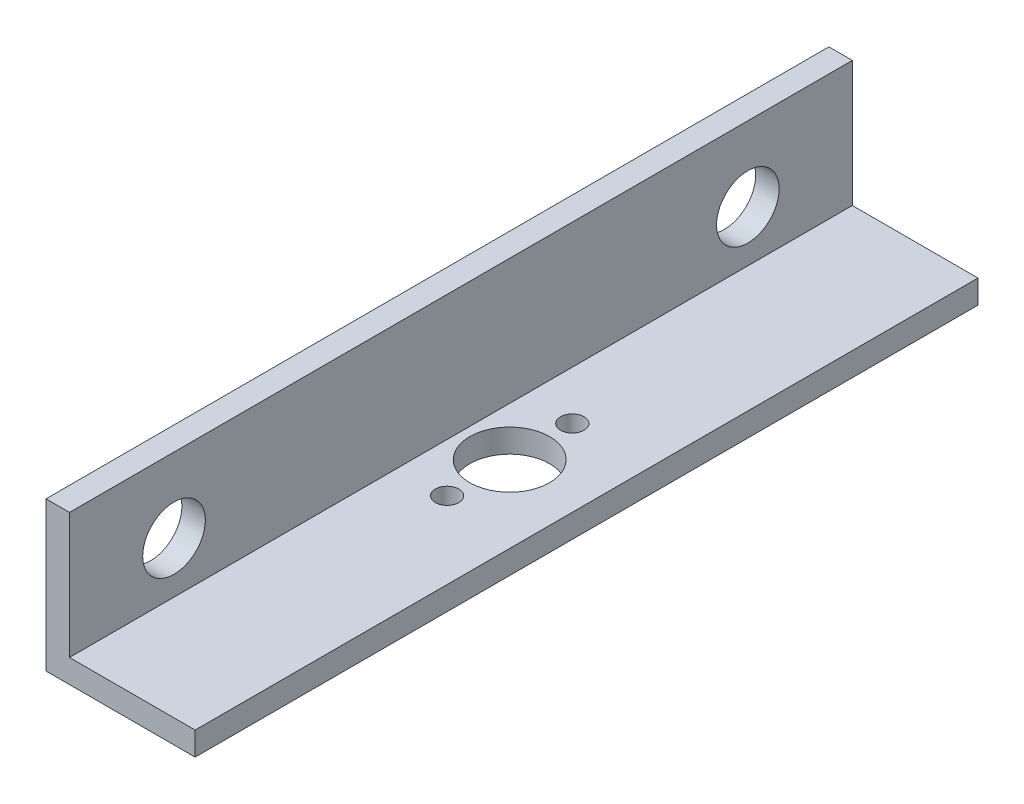
SolidWorks part; units mm, degrees
material "6061-T4 (SS)"
ref_plane "Front Plane" through (0, 0, 0) normal (0, 0, 1) x (1, 0, 0)
ref_plane "Top Plane" through (0, 0, 0) normal (0, 1, 0) x (1, 0, 0)
ref_plane "Right Plane" through (0, 0, 0) normal (1, 0, 0) x (0, 0, -1)
sketch "Sketch1" plane through (0, 0, 0) normal (0, 0, 1) x (1, 0, 0)
  line L0 (0, 0) -> (0, 19.05)
  line L2 (19.05, 0) -> (0, 0)
  dimension "D1" = 19.05
  dimension "D2" = 19.05
extrude "Extrude-Thin1" add sketch "Sketch1" along normal mid plane 100 thin
sketch "Sketch4" plane through (0, 0, 0) normal (-1, 0, 0) x (0, 0, 1)
  line L0 (0, 0) -> (0, 19.05) construction
  line L1 (50, 19.05) -> (-50, 19.05) construction
  line L2 (-36.65, 9.525) -> (36.65, 9.525) construction
  circle A0 centre (-36.65, 9.525) radius 4
  circle A1 centre (36.65, 9.525) radius 4
  point P9 (0, 9.525)
  dimension "D1" = 73.3
  dimension "D2" = 8
extrude "Cut-Extrude2" cut sketch "Sketch4" against normal up to next
sketch "Sketch3" plane through (0, 0, 0) normal (0, -1, 0) x (1, 0, 0)
  line L0 (9.23, 50) -> (9.23, -50) construction
  line L3 (19.05, 0) -> (0, 0) construction
  line L4 (19.05, 50) -> (19.05, -50) construction
  line L7 (0, 50) -> (0, -50) construction
  line L8 (19.05, 50) -> (0, 50) construction
  line L10 (19.05, -50) -> (0, -50) construction
  circle A0 centre (9.23, 0) radius 8 construction
  circle A1 centre (9.23, 0) radius 5.1
  circle A3 centre (9.23, -8) radius 1.5
  circle A5 centre (9.23, 8) radius 1.5
  point P2 (9.525, 50)
  point P3 (9.525, -50)
  point P4 (0, 0)
  point P5 (9.525, -41.6118)
  point P7 (9.525, 8)
  point P10 (0, 0)
  point P18 (0, 0)
  point P19 (0, 0)
  point P22 (9.525, -43.9682)
  point P25 (9.23, 50)
  point P28 (9.23, -50)
  point P31 (0, 0)
  point P32 (9.23, 0)
  dimension "D1" = 16
  dimension "D2" = 10.2
  dimension "D3" = 3
  dimension "D4" = 9.23
extrude "Cut-Extrude1" cut sketch "Sketch3" against normal up to surface (3 mm away) up to face at (11.025, 3, 0)
